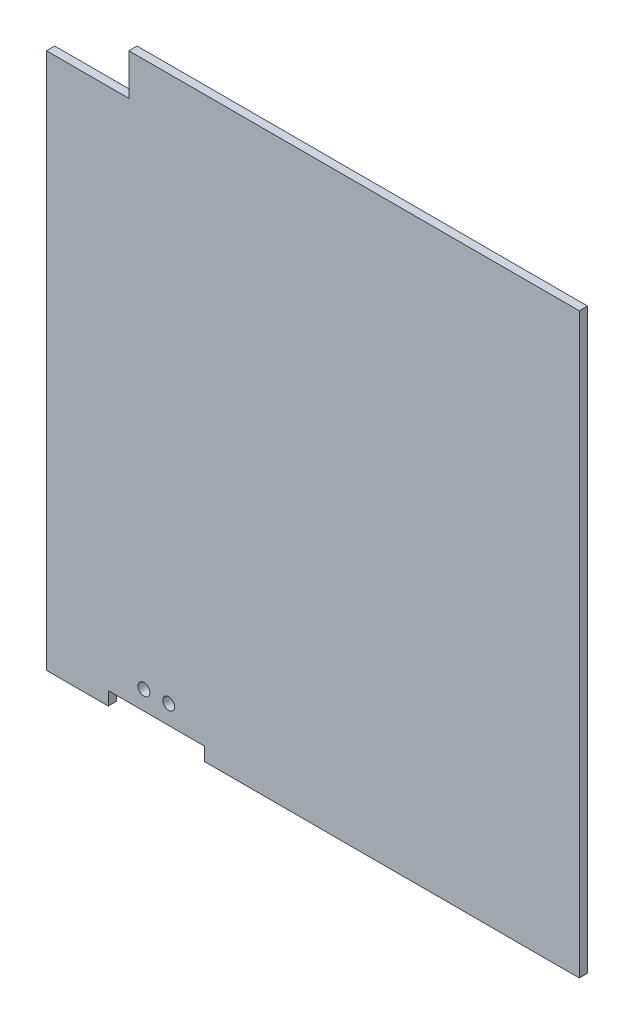
SolidWorks part; units mm, degrees
ref_plane "前视基准面" through (0, 0, 0) normal (0, 0, 1) x (1, 0, 0)
ref_plane "上视基准面" through (0, 0, 0) normal (0, 1, 0) x (1, 0, 0)
ref_plane "右视基准面" through (0, 0, 0) normal (1, 0, 0) x (0, 0, -1)
sketch "草图1" plane through (0, 0, 0) normal (0, 0, 1) x (1, 0, 0)
  line L1 (-90, 97.5) -> (90, 97.5)
  line L2 (-90, 97.5) -> (-90, -97.5)
  line L3 (-90, -97.5) -> (90, -97.5)
  line L4 (90, 97.5) -> (90, -97.5)
  line L5 (-90, 97.5) -> (90, -97.5) construction
  line L6 (-90, -97.5) -> (90, 97.5) construction
  point P0 (0, 0)
  dimension "D1" = 195
  dimension "D2" = 180
extrude "凸台-拉伸1" add sketch "草图1" along normal blind 3
sketch "草图2" plane through (0, 0, 3) normal (0, 0, 1) x (1, 0, 0)
  line L0 (-67.7, -46) -> (-40.3, -46) construction
  line L1 (-40.3, -46) -> (-40.3, -67) construction
  line L2 (-67.7, -46) -> (-67.7, -67) construction
  line L3 (-71.5, -67) -> (-67.7, -67)
  line L4 (-54, -73.8758) -> (-54, -46) construction
  line L5 (-71.5, -67) -> (-71.5, -72.5)
  line L6 (-36.5, -67) -> (-36.5, -72.5)
  line L7 (-40.3, -67) -> (-36.5, -67)
  line L8 (-82, -72.5) -> (-26, -72.5) construction
  line L9 (-71.5, -72.5) -> (-82, -72.5)
  line L10 (-82, -72.5) -> (-82, -97.5)
  line L11 (-90, -97.5) -> (90, -97.5) construction
  line L12 (-36.5, -72.5) -> (-26, -72.5)
  line L13 (-26, -72.5) -> (-26, -97.5)
  line L14 (-26, -97.5) -> (-82, -97.5)
  line L15 (-90, 97.5) -> (-90, -97.5) construction
  line L16 (-67.7, -67) -> (-40.3, -67)
  circle A0 centre (-58.5, -60.1) radius 2.15
  circle A1 centre (-49.5, -60.1) radius 2.15
  point P2 (-40.3, -56.5)
  dimension "D8" = 4.3
  dimension "D1" = 27.4
  dimension "D2" = 35
  dimension "D3" = 5.5
  dimension "D4" = 56
  dimension "D5" = 21
  dimension "D6" = 25
  dimension "D7" = 8
  dimension "D9" = 6.9
  dimension "D10" = 9
extrude "切除-拉伸1" cut sketch "草图2" against normal through all both and the other way through all
sketch "草图3" plane through (0, 0, 3) normal (0, 0, 1) x (1, 0, 0)
  line L0 (90, 97.5) -> (-90, 97.5) construction
  line L1 (-90, -97.5) -> (-100, -97.5)
  line L2 (-90, -97.5) -> (-90, 97.5)
  line L3 (-90, 97.5) -> (-100, 97.5)
  line L4 (-100, -97.5) -> (-100, 97.5)
  dimension "D1" = 10
extrude "凸台-拉伸2" add sketch "草图3" against normal up to surface (3 mm away) up to face at (-36, -51.5833, 0)
sketch "草图4" plane through (0, 0, 0) normal (0, 0, -1) x (-1, 0, 0)
  line L0 (26, -97.5) -> (26, -72.5) construction
  line L1 (-90, -97.5) -> (26, -97.5)
  line L2 (-90, -97.5) -> (-90, -119.5)
  line L3 (-90, -119.5) -> (26, -119.5)
  line L4 (26, -97.5) -> (26, -119.5)
  dimension "D1" = 22
extrude "凸台-拉伸3" add sketch "草图4" against normal up to surface (3 mm away) up to face at (-37.6667, -51.5833, 3)
sketch "草图5" plane through (0, 0, 0) normal (0, 0, -1) x (-1, 0, 0)
  line L0 (-90, -119.5) -> (-90, 97.5) construction
  line L1 (-90, -112.5) -> (26, -112.5)
  line L2 (-90, -112.5) -> (-90, -119.5)
  line L3 (-90, -119.5) -> (26, -119.5)
  line L4 (26, -112.5) -> (26, -119.5)
  dimension "D1" = 7
extrude "切除-拉伸2" cut sketch "草图5" against normal through all both and the other way through all
sketch "草图6" plane through (0, 0, 0) normal (0, 0, -1) x (-1, 0, 0)
  line L0 (24, -110.5) -> (-88, -110.5)
  line L1 (-88, -110.5) -> (-88, 95.5)
  line L2 (-88, 95.5) -> (100, 95.5)
  line L4 (100, -95.5) -> (84, -95.5)
  line L5 (24, -110.5) -> (24, -72.5)
  line L6 (24, -72.5) -> (26, -72.5)
  line L7 (82, -72.5) -> (84, -72.5)
  line L8 (84, -72.5) -> (84, -95.5)
  line L12 (-90, 97.5) -> (-90, -112.5)
  line L13 (-90, -112.5) -> (26, -112.5)
  line L14 (26, -112.5) -> (26, -72.5)
  line L15 (26, -72.5) -> (36.5, -72.5)
  line L16 (36.5, -72.5) -> (36.5, -67)
  line L17 (36.5, -67) -> (71.5, -67)
  line L18 (71.5, -67) -> (71.5, -72.5)
  line L19 (71.5, -72.5) -> (82, -72.5)
  line L20 (82, -72.5) -> (82, -97.5)
  line L21 (82, -97.5) -> (100, -97.5)
  line L22 (100, -97.5) -> (100, 97.5)
  line L23 (100, 97.5) -> (-90, 97.5)
  line L24 (-90, 97.5) -> (-90, -112.5)
  line L25 (-90, -112.5) -> (26, -112.5)
  line L26 (26, -112.5) -> (26, -72.5)
  line L27 (26, -72.5) -> (36.5, -72.5)
  line L28 (36.5, -72.5) -> (36.5, -67)
  line L29 (36.5, -67) -> (71.5, -67)
  line L30 (71.5, -67) -> (71.5, -72.5)
  line L31 (71.5, -72.5) -> (82, -72.5)
  line L32 (82, -72.5) -> (82, -97.5)
  line L33 (82, -97.5) -> (100, -97.5)
  line L34 (100, -97.5) -> (100, 97.5)
  line L35 (100, 97.5) -> (-90, 97.5)
  point P2 (26, -92.5)
  line M21 (-90, 97.5) -> (-90, -112.5)
  line M22 (-90, -112.5) -> (26, -112.5)
  line M23 (26, -112.5) -> (26, -72.5)
  line M29 (82, -72.5) -> (82, -97.5)
  line M30 (82, -97.5) -> (100, -97.5)
  line M31 (100, -97.5) -> (100, 97.5)
  line M32 (100, 97.5) -> (-90, 97.5)
  dimension "D2" = 2
  dimension "D4" = 2
  dimension "D5" = 2
  dimension "D6" = 2
  dimension "D7" = 2
  dimension "D8" = 2
  dimension "D1" = 0
extrude "切除-拉伸3" cut sketch "草图6" against normal through all both and the other way through all contours L8 L7 L4 M29 M30 M31 | L6 L5 L0 L1 L2 M31 M32 M21 M22 M23
sketch "草图7" plane through (0, 0, 0) normal (0, 0, -1) x (-1, 0, 0)
  line L0 (100, -95.5) -> (100, 95.5) construction
  line L1 (-88, -110.5) -> (100, -110.5)
  line L2 (-88, -110.5) -> (-88, -71.8733)
  line L3 (-88, -71.8733) -> (100, -71.8733)
  line L4 (100, -110.5) -> (100, -71.8733)
extrude "切除-拉伸4" cut sketch "草图7" against normal through all both and the other way through all
sketch "草图8" plane through (0, 0, 0) normal (0, 0, -1) x (-1, 0, 0)
  line L0 (100, -71.8733) -> (100, 95.5) construction
  line L1 (-88, 95.5) -> (100, 95.5)
  line L3 (-80, 123.5) -> (100, 123.5)
  line L4 (100, 95.5) -> (100, 123.5)
  line L6 (-88, -71.8733) -> (-100, -71.8733)
  line L7 (-88, -71.8733) -> (-88, 95.5)
  line L8 (-80, 123.5) -> (-100, 123.5)
  line L9 (-100, -71.8733) -> (-100, 123.5)
  dimension "D1" = 12
  dimension "D2" = 28
extrude "凸台-拉伸4" add sketch "草图8" against normal up to surface (3 mm away) up to face at (-30, -28.8116, 3)
sketch "草图9" plane through (0, 0, 0) normal (0, 0, -1) x (-1, 0, 0)
  line L0 (71.5, -71.8733) -> (100, -71.8733) construction
  line L1 (94, -71.8733) -> (100, -71.8733)
  line L2 (94, -71.8733) -> (94, 123.5)
  line L3 (94, 123.5) -> (100, 123.5)
  line L4 (100, -71.8733) -> (100, 123.5)
  line L5 (100, 123.5) -> (-100, 123.5) construction
  dimension "D1" = 6
extrude "切除-拉伸5" cut sketch "草图9" against normal through all both and the other way through all
sketch "草图10" plane through (0, 0, 0) normal (0, 0, -1) x (-1, 0, 0)
  line L0 (94, -71.8733) -> (94, 123.5) construction
  line L1 (-100, -71.8733) -> (94, -71.8733)
  line L2 (-100, -71.8733) -> (-100, -70.8733)
  line L3 (-100, -70.8733) -> (94, -70.8733)
  line L4 (94, -71.8733) -> (94, -70.8733)
  dimension "D1" = 1
sketch "草图11" plane through (0, 0, 0) normal (0, 0, -1) x (-1, 0, 0)
  line L0 (94, 123.5) -> (-100, 123.5) construction
  line L1 (64, 123.5) -> (-100, 123.5)
  line L2 (64, 123.5) -> (64, 138.5)
  line L3 (64, 138.5) -> (-100, 138.5)
  line L4 (-100, 123.5) -> (-100, 138.5)
  line L5 (-100, 123.5) -> (-100, -71.8733) construction
  line L6 (94, -71.8733) -> (94, 123.5) construction
  dimension "D1" = 15
  dimension "D2" = 30
extrude "凸台-拉伸5" add sketch "草图11" against normal up to surface (3 mm away) up to face at (-25.5, -21.8116, 3)
